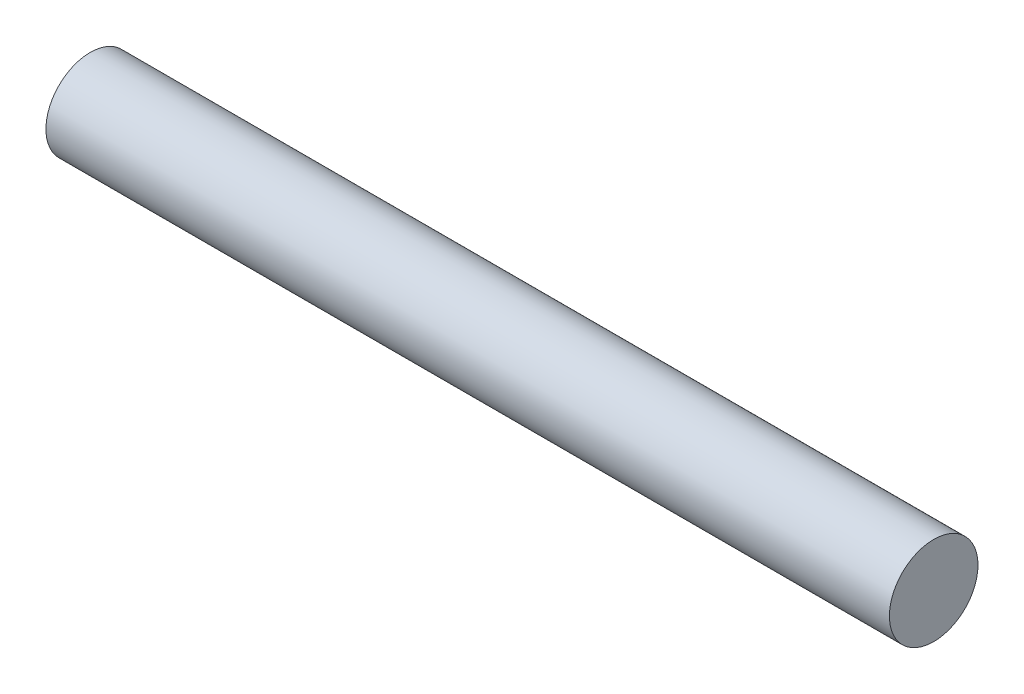
SolidWorks part; units mm, degrees
ref_plane "Front Plane" through (0, 0, 0) normal (0, 0, 1) x (1, 0, 0)
ref_plane "Top Plane" through (0, 0, 0) normal (0, 1, 0) x (1, 0, 0)
ref_plane "Right Plane" through (0, 0, 0) normal (1, 0, 0) x (0, 0, -1)
sketch "Sketch1" plane through (0, 0, 0) normal (1, 0, 0) x (0, 0, -1)
  circle A0 centre (0, 0) radius 0.9779
  dimension "D1" = 1.9558
extrude "Boss-Extrude1" add sketch "Sketch1" along normal mid plane 18.6182
